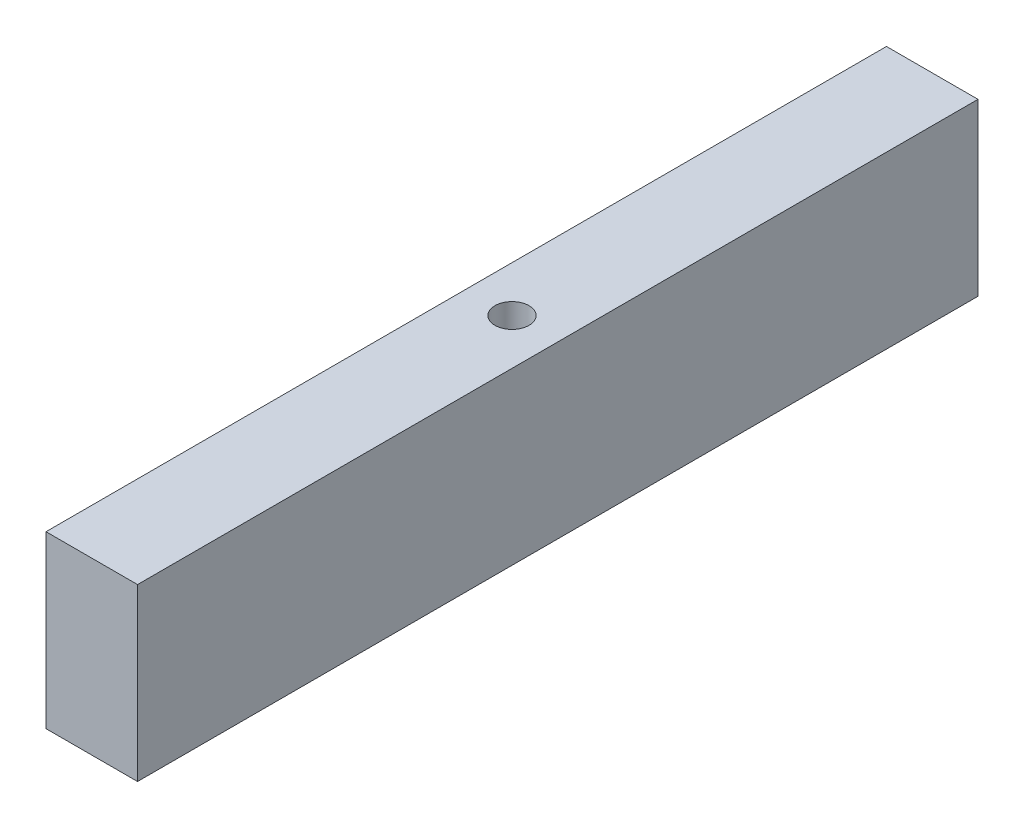
SolidWorks part; units mm, degrees
material "Gray Cast Iron"
ref_plane "Front Plane" through (0, 0, 0) normal (0, 0, 1) x (1, 0, 0)
ref_plane "Top Plane" through (0, 0, 0) normal (0, 1, 0) x (1, 0, 0)
ref_plane "Right Plane" through (0, 0, 0) normal (1, 0, 0) x (0, 0, -1)
sketch "Sketch1" plane through (0, 0, 0) normal (0, 0, 1) x (1, 0, 0)
  line L0 (-11, 0) -> (11, 0)
  line L1 (11, 0) -> (11, 41)
  line L2 (11, 41) -> (-11, 41)
  line L3 (-11, 41) -> (-11, 0)
  dimension "D1" = 22
  dimension "D2" = 41
  dimension "D3" = 11
extrude "Boss-Extrude1" add sketch "Sketch1" along normal mid plane 202
sketch "Sketch2" plane through (0, 0, 0) normal (0, 1, 0) x (1, 0, 0)
  circle A0 centre (0, 0) radius 4.1
  dimension "D1" = 8.2
extrude "Cut-Extrude1" cut sketch "Sketch2" against normal mid plane 92
